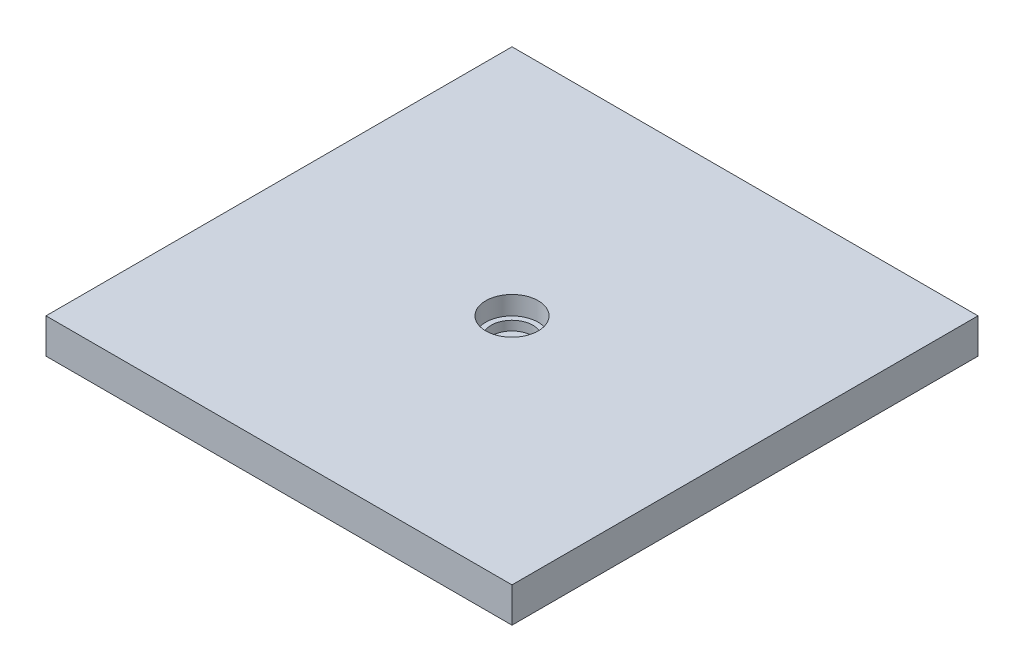
SolidWorks part; units mm, degrees
ref_plane "Front Plane" through (0, 0, 0) normal (0, 0, 1) x (1, 0, 0)
ref_plane "Top Plane" through (0, 0, 0) normal (0, 1, 0) x (1, 0, 0)
ref_plane "Right Plane" through (0, 0, 0) normal (1, 0, 0) x (0, 0, -1)
sketch "Sketch2" plane through (0, 0, 0) normal (0, 1, 0) x (1, 0, 0)
  line L1 (-100, 100) -> (100, 100)
  line L2 (-100, 100) -> (-100, -100)
  line L3 (-100, -100) -> (100, -100)
  line L4 (100, 100) -> (100, -100)
  point P4 (0, 100)
  point P6 (100, 0)
  dimension "D1" = 200
  dimension "D2" = 200
extrude "Boss-Extrude1" add sketch "Sketch2" along normal blind 15
sketch "Sketch3" plane through (0, 15, 0) normal (0, 1, 0) x (1, 0, 0)
  circle A0 centre (0, 0) radius 11.25
  dimension "D1" = 22.5
extrude "Cut-Extrude1" cut sketch "Sketch3" against normal blind 8
sketch "Sketch4" plane through (0, 7, 0) normal (0, 1, 0) x (1, 0, 0)
  circle A0 centre (0, 0) radius 9
  dimension "D1" = 18
extrude "Cut-Extrude2" cut sketch "Sketch4" against normal blind 4
